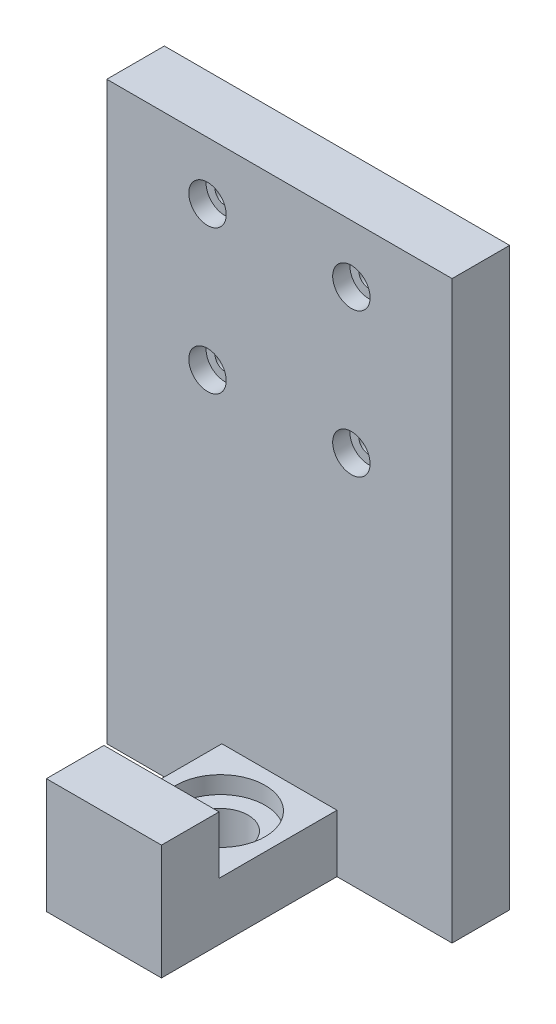
SolidWorks part; units mm, degrees
ref_plane "Front" through (0, 0, 0) normal (0, 0, 1) x (1, 0, 0)
ref_plane "Top" through (0, 0, 0) normal (0, 1, 0) x (1, 0, 0)
ref_plane "Right" through (0, 0, 0) normal (1, 0, 0) x (0, 0, -1)
sketch "Sketch1" plane through (0, 0, 0) normal (0, 0, 1) x (1, 0, 0)
  line L1 (-39.2633, 78.304) -> (20.7367, 78.304)
  line L2 (-39.2633, 78.304) -> (-39.2633, -21.696)
  line L3 (-39.2633, -21.696) -> (20.7367, -21.696)
  line L4 (20.7367, 78.304) -> (20.7367, -21.696)
  dimension "D1" = 100
  dimension "D2" = 60
extrude "Extrude1" add sketch "Sketch1" along normal blind 10
sketch "Sketch2" plane through (0, 0, 10) normal (0, 0, 1) x (1, 0, 0)
  line L0 (-39.2633, -21.696) -> (20.7367, -21.696) construction
  line L1 (-19.2633, -11.696) -> (0.7367, -11.696)
  line L2 (-19.2633, -11.696) -> (-19.2633, -21.696)
  line L3 (-19.2633, -21.696) -> (0.7367, -21.696)
  line L4 (0.7367, -11.696) -> (0.7367, -21.696)
  line L5 (-39.2633, 78.304) -> (-39.2633, -21.696) construction
  dimension "D1" = 10
  dimension "D2" = 20
  dimension "D3" = 20
extrude "Extrude2" add sketch "Sketch2" along normal blind 30.5
sketch "Sketch4" plane through (0, -11.696, 0) normal (0, 1, 0) x (1, 0, 0)
  line L0 (0.7367, -40.5) -> (0.7367, -10) construction
  line L1 (-19.2633, -40.5) -> (0.7367, -40.5)
  line L2 (-19.2633, -40.5) -> (-19.2633, -30.5)
  line L3 (-19.2633, -30.5) -> (0.7367, -30.5)
  line L4 (0.7367, -40.5) -> (0.7367, -30.5)
  dimension "D1" = 10
extrude "Extrude3" add sketch "Sketch4" along normal blind 10
sketch "Sketch5" plane through (0, -11.696, 0) normal (0, 1, 0) x (1, 0, 0)
  line L0 (0.7367, -30.5) -> (0.7367, -10) construction
  line L1 (0.7367, -10) -> (-19.2633, -10) construction
  circle A0 centre (-9.2633, -20.25) radius 7.75
  dimension "D1" = 15.5
  dimension "D2" = 10
  dimension "D3" = 10.25
extrude "Cut-Extrude1" cut sketch "Sketch5" against normal blind 3
sketch "Sketch6" plane through (0, -14.696, 0) normal (0, 1, 0) x (1, 0, 0)
  line L0 (-19.2633, -30.5) -> (-19.2633, -10) construction
  line L1 (0.7367, -30.5) -> (-19.2633, -30.5) construction
  circle A0 centre (-9.2633, -20.25) radius 4.8
  point P2 (-19.2633, -20.25)
  dimension "D1" = 9.6
  dimension "D2" = 10
  dimension "D3" = 10.25
extrude "Cut-Extrude2" cut sketch "Sketch6" against normal through all
hole_wizard "CBORE for M3 SHCS1" positions "3DSketch1" profile "Sketch9" counterbore size "M3" standard "Ansi Metric" end condition through all
sketch3d "3DSketch1"
  line L0 (20.7367, 78.304, 10) -> (-39.2633, 78.304, 10) construction
  line L1 (-39.2633, 78.304, 10) -> (-39.2633, -21.696, 10) construction
  point P0 (-21.7633, 68.304, 10)
  point P2 (-21.7633, 43.304, 10)
  point P4 (3.2367, 68.304, 10)
  point P6 (3.2367, 43.304, 10)
  dimension "D1" = 25
  dimension "D2" = 25
  dimension "D3" = 25
  dimension "D4" = 25
  dimension "D5" = 10
  dimension "D6" = 17.5
sketch "Sketch9" plane through (-21.7633, 68.304, 10) normal (1, 0, 0) x (0, -1, 0)
  line L0 (0, 0) -> (0, 10)
  line L1 (0, 10) -> (1.7, 10)
  line L3 (1.7, 10) -> (1.7, 3)
  line L4 (1.7, 3) -> (3.25, 3)
  line L5 (3.25, 3) -> (3.25, 0)
  line L7 (3.25, 0) -> (0, 0)
  line L11 (0, -6.35) -> (0, 107.95) construction
  dimension "Thru Hole Dia." = 3.4
  dimension "Thru Hole Depth" = 10
  dimension "C'Bore Dia." = 6.5
  dimension "C'Bore Depth" = 3
